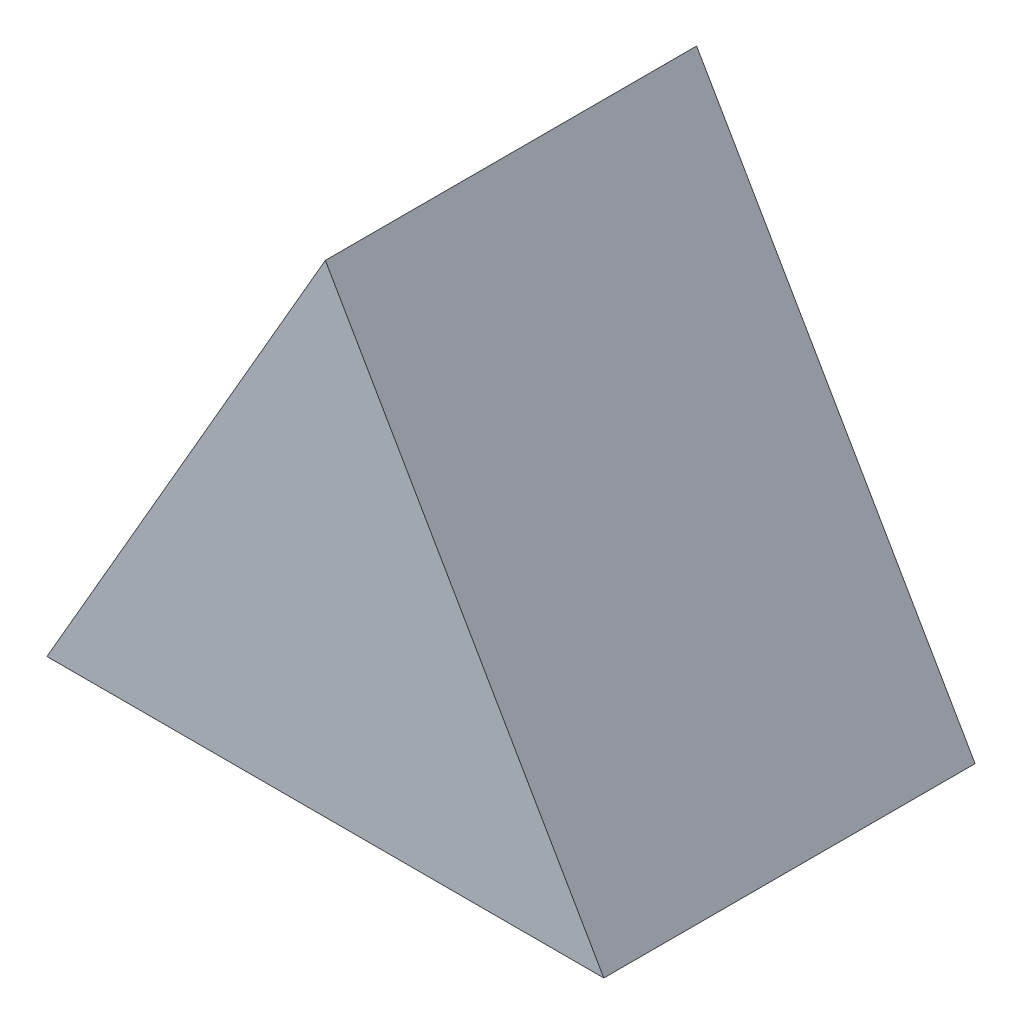
SolidWorks part; units mm, degrees
material "AISI 1020"
ref_plane "Front Plane" through (0, 0, 0) normal (0, 0, 1) x (1, 0, 0)
ref_plane "Top Plane" through (0, 0, 0) normal (0, 1, 0) x (1, 0, 0)
ref_plane "Right Plane" through (0, 0, 0) normal (1, 0, 0) x (0, 0, -1)
sketch "Sketch1" plane through (0, 0, 0) normal (0, 0, 1) x (1, 0, 0)
  line L1 (0, 34.641) -> (-30, -17.3205)
  line L2 (-30, -17.3205) -> (30, -17.3205)
  line L3 (30, -17.3205) -> (0, 34.641)
  circle A0 centre (0, 0) radius 17.3205 construction
  dimension "D1" = 60
extrude "Boss-Extrude1" add sketch "Sketch1" along normal blind 40
equation "\"A\"= 100"
equation "\"B\"= 100"
equation "\"C\"= 100"
equation "\"D\"= 100"
equation "\"E\"= 100"
